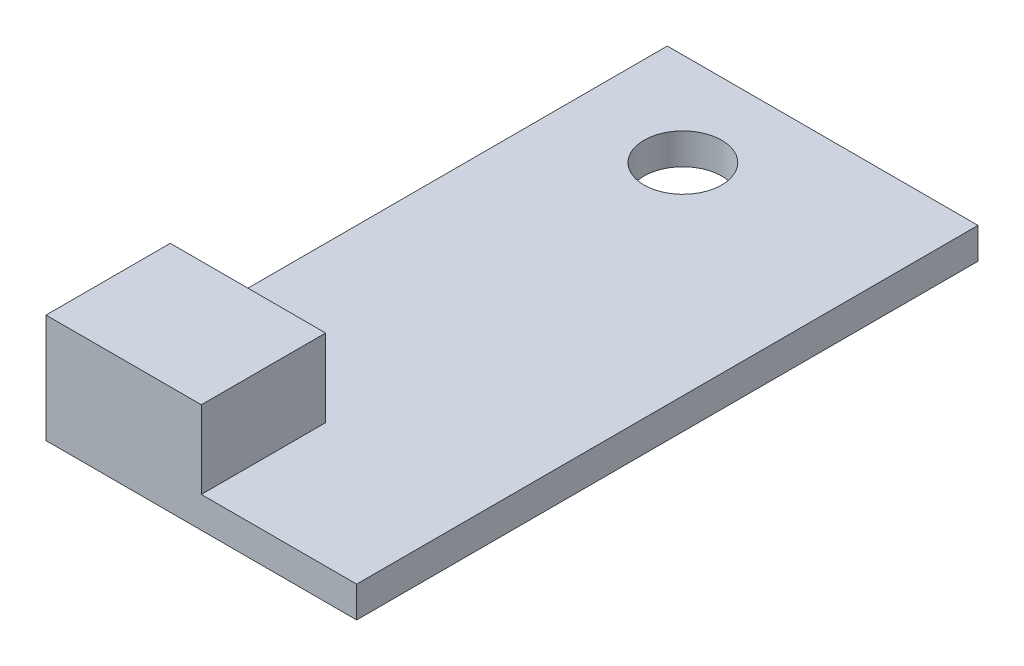
SolidWorks part; units mm, degrees
ref_plane "Front Plane" through (0, 0, 0) normal (0, 0, 1) x (1, 0, 0)
ref_plane "Top Plane" through (0, 0, 0) normal (0, 1, 0) x (1, 0, 0)
ref_plane "Right Plane" through (0, 0, 0) normal (1, 0, 0) x (0, 0, -1)
sketch "Sketch1" plane through (0, 0, 0) normal (0, 1, 0) x (1, 0, 0)
  line L1 (0, 0) -> (100, 0)
  line L2 (0, 0) -> (0, 200)
  line L3 (0, 200) -> (100, 200)
  line L4 (100, 0) -> (100, 200)
  dimension "D1" = 100
  dimension "D2" = 200
extrude "Boss-Extrude1" add sketch "Sketch1" along normal blind 10
sketch "Sketch2" plane through (0, 10, 0) normal (0, 1, 0) x (1, 0, 0)
  line L1 (0, 0) -> (50, 0)
  line L2 (0, 0) -> (0, 40)
  line L3 (0, 40) -> (50, 40)
  line L4 (50, 0) -> (50, 40)
  dimension "D1" = 50
  dimension "D2" = 40
extrude "Boss-Extrude2" add sketch "Sketch2" along normal blind 25
hole_wizard "Ø25.0 (25) Diameter Hole1" positions "Sketch4" profile "Sketch3" hole size "Ø25.0" standard "ANSI Metric" end condition through all
sketch "Sketch4" plane through (0, 10, 0) normal (0, 1, 0) x (1, 0, 0)
  line L0 (0, 200) -> (0, 40) construction
  line L1 (100, 200) -> (0, 200) construction
  point P0 (35, 170)
  dimension "D1" = 35
  dimension "D2" = 30
sketch "Sketch3" plane through (35, 10, -170) normal (1, 0, 0) x (0, 0, 1)
  line L0 (0, 0) -> (0, 10)
  line L1 (0, 10) -> (12.5, 10)
  line L2 (12.5, 10) -> (12.5, 0)
  line L5 (12.5, 0) -> (0, 0)
  line L11 (0, -6.35) -> (0, 107.95) construction
  dimension "Thru Hole Dia." = 25
  dimension "Thru Hole Depth" = 10
